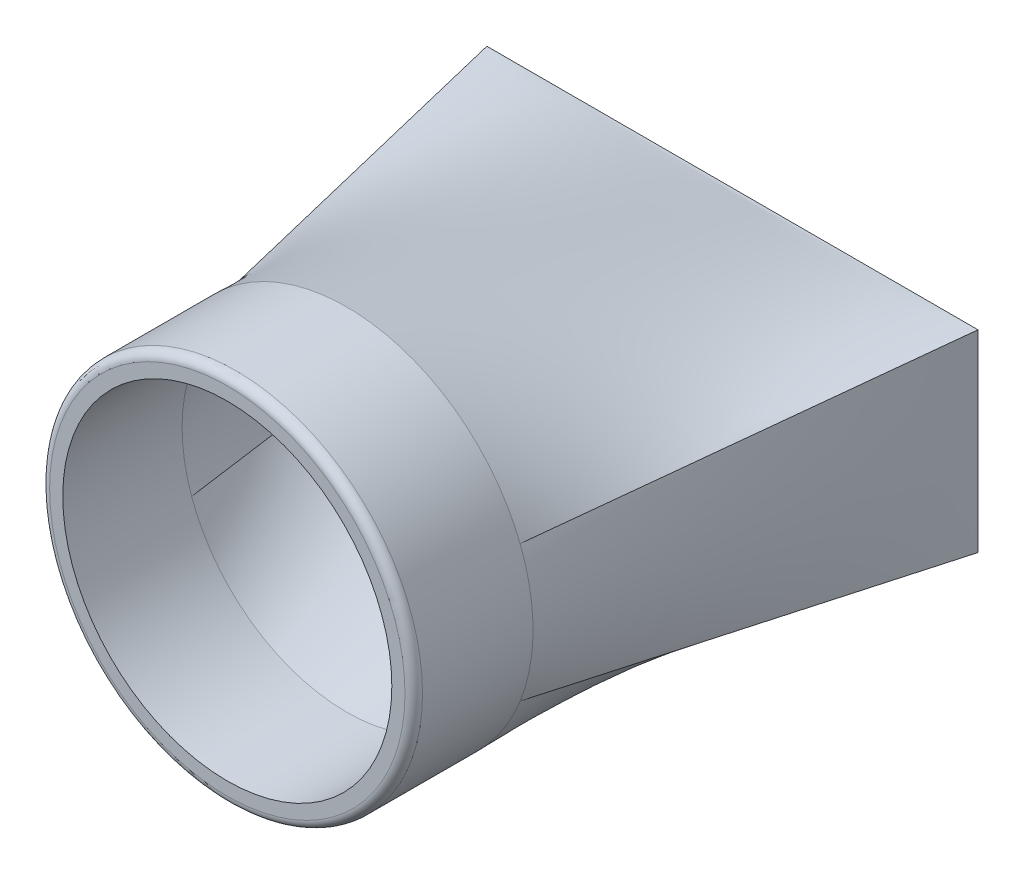
SolidWorks part; units mm, degrees
material "ABS"
ref_plane "Front Plane" through (0, 0, 0) normal (0, 0, 1) x (1, 0, 0)
ref_plane "Top Plane" through (0, 0, 0) normal (0, 1, 0) x (1, 0, 0)
ref_plane "Right Plane" through (0, 0, 0) normal (1, 0, 0) x (0, 0, -1)
ref_plane "Plane1" through (0, 0, -110) normal (0, 0, 1) x (1, 0, 0)
sketch "Sketch6" plane through (0, 0, 0) normal (0, 0, 1) x (1, 0, 0)
  circle A0 centre (0, 0) radius 53.15
  dimension "D1" = 106.3
sketch "Sketch7" plane through (0, 0, -110) normal (0, 0, 1) x (1, 0, 0)
  line L1 (-70, 27.5) -> (70, 27.5)
  line L2 (-70, 27.5) -> (-70, -27.5)
  line L3 (-70, -27.5) -> (70, -27.5)
  line L4 (70, 27.5) -> (70, -27.5)
  line L5 (-70, 27.5) -> (70, -27.5) construction
  line L6 (-70, -27.5) -> (70, 27.5) construction
  point P0 (0, 0)
  dimension "D1" = 140
  dimension "D2" = 55
loft "Loft1" add profiles "Sketch7", "Sketch6"
sketch "Sketch8" plane through (0, 0, 0) normal (0, 0, 1) x (1, 0, 0)
  line L0 (0, 0) -> (65.9845, 0) construction
  line L1 (0, 0) -> (-78.7926, 0) construction
  line L2 (53.15, 0) -> (53.15, -13.535) construction
  line L3 (53.15, -13.535) -> (53.15, 11.7573) construction
  circle A0 centre (0, 0) radius 46.9
  arc A2 (49.4694, -19.4344) -> (49.4694, 19.4344) centre (0, 0) ccw construction
  dimension "D1" = 93.8
sketch "Sketch12" plane through (0, 0, -110) normal (0, 0, -1) x (-1, 0, 0)
  line L1 (-66, 23.5) -> (66, 23.5)
  line L2 (-66, 23.5) -> (-66, -23.5)
  line L3 (-66, -23.5) -> (66, -23.5)
  line L4 (66, 23.5) -> (66, -23.5)
  line L5 (-66, 23.5) -> (66, -23.5) construction
  line L6 (-66, -23.5) -> (66, 23.5) construction
  point P0 (0, 0)
  dimension "D1" = 132
  dimension "D2" = 47
loft "Cut-Loft1" cut profiles "Sketch8", "Sketch12"
sketch "Sketch18" plane through (0, 0, -110) normal (0, 0, -1) x (-1, 0, 0)
  line L0 (-66, -23.5) -> (-70, -23.5) construction
  line L1 (-70, -27.5) -> (-70, 27.5) construction
  line L2 (-68, -23.5) -> (-68, 23.4798) construction
  line L3 (66, -23.5) -> (70, -23.5) construction
  line L4 (70, 27.5) -> (70, -27.5) construction
  line L5 (68, -23.5) -> (68, 26.8674) construction
  line L6 (0, 0) -> (-87.6335, 0) construction
  line L7 (-87.6335, 0) -> (79.9265, 0) construction
  point P20 (-68, -0.0101)
  point P22 (68, 0)
hole_wizard "M2 Tapped Hole1" positions "Sketch18" profile "Sketch21" tap size "M2" standard "ISO"
sketch "Sketch21" plane through (-68, 0, -110) normal (1, 0, 0) x (0, 1, 0)
  line L0 (0, 0) -> (0, 6.4807)
  line L1 (0, 6.4807) -> (0.8, 6)
  line L2 (0.8, 6) -> (0.8, 0.225)
  line L3 (0.8, 0.225) -> (1.025, 0)
  line L5 (1.025, 0) -> (0, 0)
  line L6 (-0.8, 0.225) -> (-1.025, 0) construction
  line L10 (0, 6.4807) -> (-0.8, 6) construction
  line L11 (0, -6.35) -> (0, 107.95) construction
  dimension "Tap Drill Dia." = 1.6
  dimension "Tap Drill Depth" = 6
  dimension "Near C'Sink Dia." = 2.05
  dimension "Near C'Sink Angle" = 90
  dimension "Drill Angle" = 118
cosmetic thread "Hole Thread1" parameters "D1"=4, "D2"=2
cosmetic thread "Hole Thread2" parameters "D1"=4, "D2"=2
sketch "Sketch28" plane through (0, 0, 0) normal (0, 0, 1) x (1, 0, 0)
  circle A0 centre (0, 0) radius 46.9
  circle A1 centre (0, 0) radius 53.15
  dimension "D1" = 106.3
  dimension "D2" = 93.8
extrude "Boss-Extrude2" add sketch "Sketch28" along normal blind 34
fillet "Fillet1" radius 2.5 1 edges at (53.15, 0, 34)
